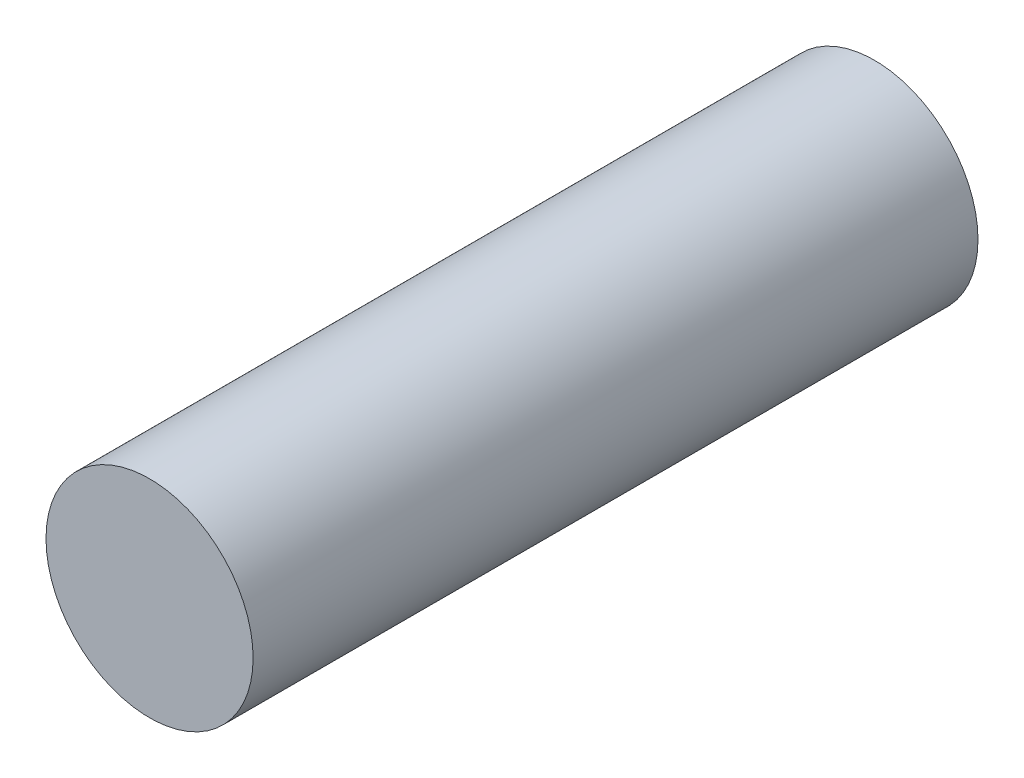
SolidWorks part; units mm, degrees
ref_plane "Front Plane" through (0, 0, 0) normal (0, 0, 1) x (1, 0, 0)
ref_plane "Top Plane" through (0, 0, 0) normal (0, 1, 0) x (1, 0, 0)
ref_plane "Right Plane" through (0, 0, 0) normal (1, 0, 0) x (0, 0, -1)
sketch "Sketch1" plane through (0, 0, 0) normal (0, 0, 1) x (1, 0, 0)
  circle A0 centre (0, 0) radius 5
extrude "Boss-Extrude1" add sketch "Sketch1" along normal blind 35
